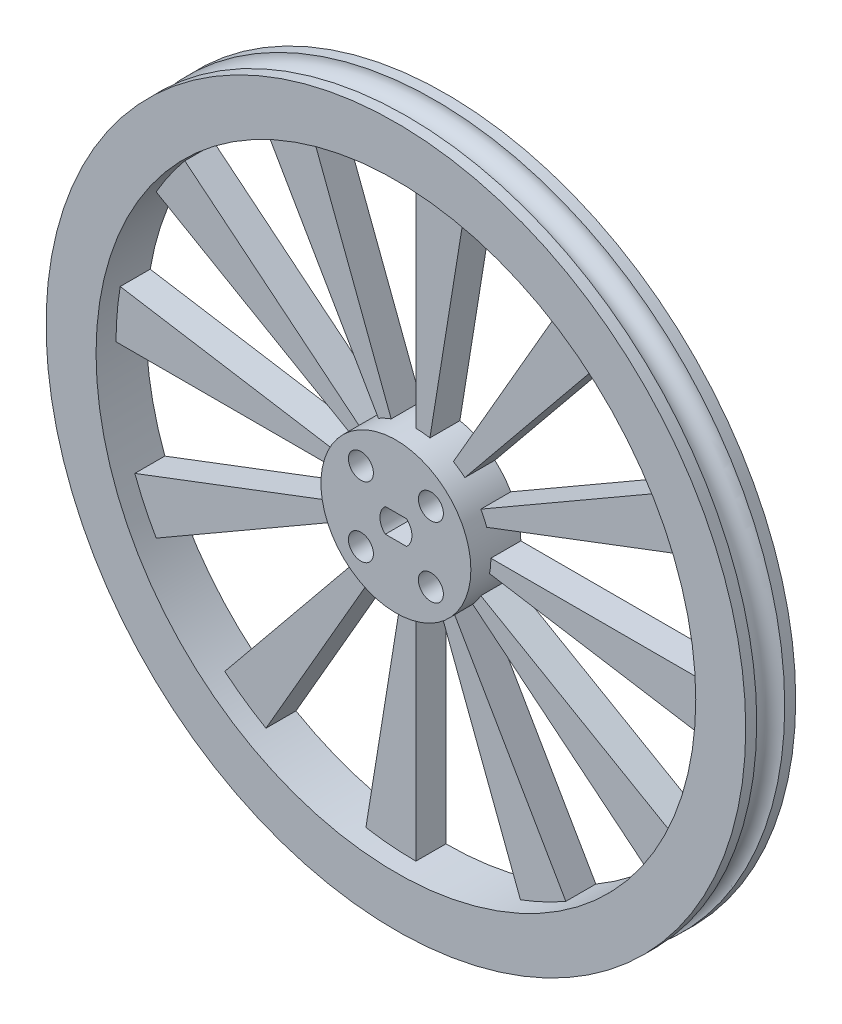
SolidWorks part; units mm, degrees
ref_plane "Front Plane" through (0, 0, 0) normal (0, 0, 1) x (1, 0, 0)
ref_plane "Top Plane" through (0, 0, 0) normal (0, 1, 0) x (1, 0, 0)
ref_plane "Right Plane" through (0, 0, 0) normal (1, 0, 0) x (0, 0, -1)
sketch "Sketch1" plane through (0, 0, 0) normal (0, 0, 1) x (1, 0, 0)
  line L0 (-1.344, 1.524) -> (1.344, 1.524)
  line L1 (-2.032, 0) -> (2.032, 0) construction
  line L2 (-1.344, -1.524) -> (1.344, -1.524)
  circle A0 centre (0, 0) radius 44.45
  arc A1 (-1.344, 1.524) -> (-1.344, -1.524) centre (0, 0) ccw
  circle A2 centre (0, 0) radius 38.1
  circle A3 centre (0, 0) radius 9.525
  arc A4 (1.344, -1.524) -> (1.344, 1.524) centre (0, 0) ccw
  dimension "D1" = 88.9
  dimension "D2" = 4.064
  dimension "D3" = 76.2
  dimension "D4" = 19.05
  dimension "D5" = 1.524
extrude "Boss-Extrude1" add sketch "Sketch1" along normal blind 3.81 and the other way blind 2.54 contours A0 A2 | A3 A1
sketch "Sketch2" plane through (0, 0, 0) normal (0, 0, 1) x (1, 0, 0)
  line L0 (0, 9.525) -> (0, 38.1)
  line L1 (1.778, 9.3576) -> (6.35, 37.5671)
  line L4 (0, 9.525) -> (1.778, 9.3576)
  line L6 (4.7625, 8.2489) -> (19.05, 32.9956)
  line L7 (6.2186, 7.2149) -> (24.2828, 29.3591)
  line L8 (4.7625, 8.2489) -> (6.2186, 7.2149)
  line L9 (8.2489, 4.7625) -> (32.9956, 19.05)
  line L10 (8.9929, 3.139) -> (35.7091, 13.2843)
  line L11 (8.2489, 4.7625) -> (8.9929, 3.139)
  line L12 (9.525, 0) -> (38.1, 0)
  line L13 (9.3576, -1.778) -> (37.5671, -6.35)
  line L14 (9.525, 0) -> (9.3576, -1.778)
  line L15 (8.2489, -4.7625) -> (32.9956, -19.05)
  line L16 (7.2149, -6.2186) -> (29.3591, -24.2828)
  line L17 (8.2489, -4.7625) -> (7.2149, -6.2186)
  line L18 (4.7625, -8.2489) -> (19.05, -32.9956)
  line L19 (3.139, -8.9929) -> (13.2843, -35.7091)
  line L20 (4.7625, -8.2489) -> (3.139, -8.9929)
  line L21 (0, -9.525) -> (0, -38.1)
  line L22 (-1.778, -9.3576) -> (-6.35, -37.5671)
  line L23 (0, -9.525) -> (-1.778, -9.3576)
  line L24 (-4.7625, -8.2489) -> (-19.05, -32.9956)
  line L25 (-6.2186, -7.2149) -> (-24.2828, -29.3591)
  line L26 (-4.7625, -8.2489) -> (-6.2186, -7.2149)
  line L27 (-8.2489, -4.7625) -> (-32.9956, -19.05)
  line L28 (-8.9929, -3.139) -> (-35.7091, -13.2843)
  line L29 (-8.2489, -4.7625) -> (-8.9929, -3.139)
  line L30 (-9.525, 0) -> (-38.1, 0)
  line L31 (-9.3576, 1.778) -> (-37.5671, 6.35)
  line L32 (-9.525, 0) -> (-9.3576, 1.778)
  line L33 (-8.2489, 4.7625) -> (-32.9956, 19.05)
  line L34 (-7.2149, 6.2186) -> (-29.3591, 24.2828)
  line L35 (-8.2489, 4.7625) -> (-7.2149, 6.2186)
  line L36 (-4.7625, 8.2489) -> (-19.05, 32.9956)
  line L37 (-3.139, 8.9929) -> (-13.2843, 35.7091)
  line L38 (-4.7625, 8.2489) -> (-3.139, 8.9929)
  circle A0 centre (0, 0) radius 9.525 construction
  circle A1 centre (0, 0) radius 38.1 construction
  arc A2 (6.35, 37.5671) -> (0, 38.1) centre (0, 0) ccw
  arc A3 (24.2828, 29.3591) -> (19.05, 32.9956) centre (0, 0) ccw
  arc A4 (35.7091, 13.2843) -> (32.9956, 19.05) centre (0, 0) ccw
  arc A5 (37.5671, -6.35) -> (38.1, 0) centre (0, 0) ccw
  arc A6 (29.3591, -24.2828) -> (32.9956, -19.05) centre (0, 0) ccw
  arc A7 (13.2843, -35.7091) -> (19.05, -32.9956) centre (0, 0) ccw
  arc A8 (-6.35, -37.5671) -> (0, -38.1) centre (0, 0) ccw
  arc A9 (-24.2828, -29.3591) -> (-19.05, -32.9956) centre (0, 0) ccw
  arc A10 (-35.7091, -13.2843) -> (-32.9956, -19.05) centre (0, 0) ccw
  arc A11 (-37.5671, 6.35) -> (-38.1, 0) centre (0, 0) ccw
  arc A12 (-29.3591, 24.2828) -> (-32.9956, 19.05) centre (0, 0) ccw
  arc A13 (-13.2843, 35.7091) -> (-19.05, 32.9956) centre (0, 0) ccw
  point P55 (0, 0)
  dimension "D1" = 1.778
  dimension "D2" = 6.35
  dimension "D3" = 12
extrude "Boss-Extrude2" add sketch "Sketch2" along normal blind 1.27 and the other way blind 2.54
sketch "Sketch4" plane through (0, 0, 0) normal (0, 0, 1) x (1, 0, 0)
  circle A0 centre (-4.445, 4.445) radius 1.5875
  circle A1 centre (4.445, 4.445) radius 1.5875
  circle A2 centre (4.445, -4.445) radius 1.5875
  circle A3 centre (-4.445, -4.445) radius 1.5875
  dimension "D1" = 3.175
  dimension "D2" = 8.89
  dimension "D3" = 8.89
  dimension "D4" = 4.445
  dimension "D5" = 4.445
extrude "Cut-Extrude1" cut sketch "Sketch4" against normal blind 5.08 and the other way blind 5.08
sketch "Sketch6" plane through (0, 0, 0) normal (1, 0, 0) x (0, 0, -1)
  line L0 (2.54, 44.45) -> (-3.81, 44.45) construction
  line L1 (-17.9237, 0) -> (17.9237, 0) construction
  circle A0 centre (-0.635, 44.45) radius 1.778
  dimension "D1" = 3.556
revolve "Cut-Revolve1" cut sketch "Sketch6" angle 360 about L1
